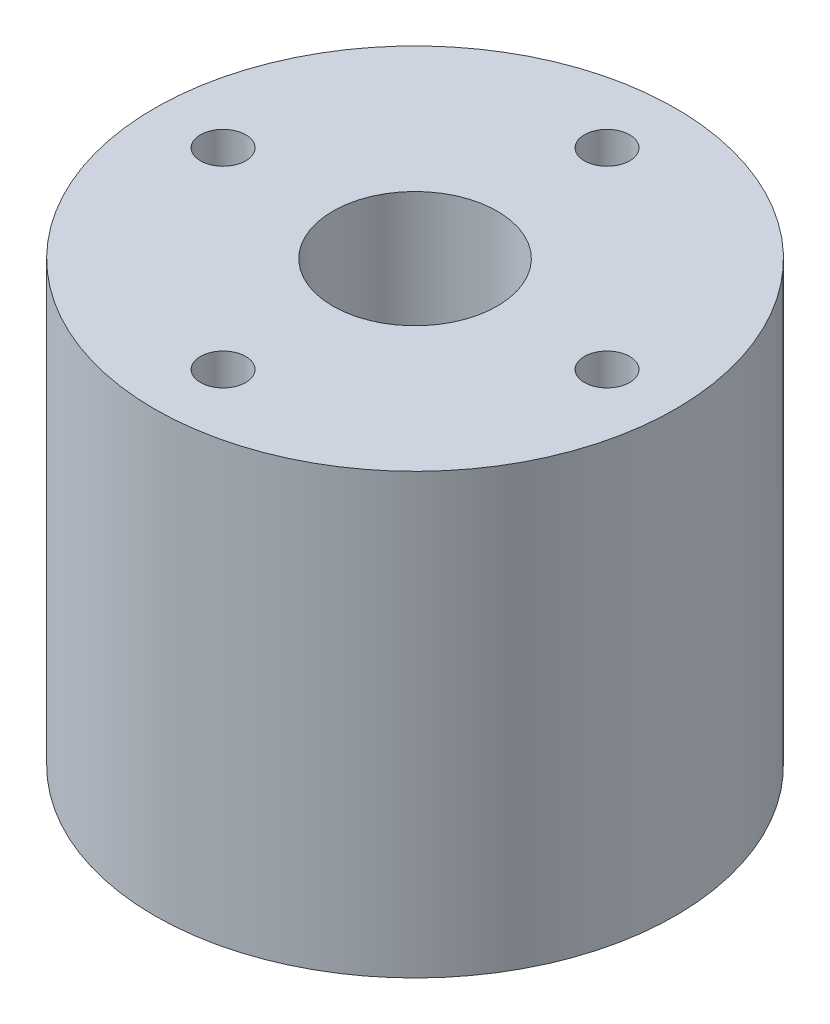
SolidWorks part; units mm, degrees
material "S45C表面镀硬铬"
ref_plane "前基準面" through (0, 0, 0) normal (0, 0, 1) x (1, 0, 0)
ref_plane "上基準面" through (0, 0, 0) normal (0, 1, 0) x (1, 0, 0)
ref_plane "右基準面" through (0, 0, 0) normal (1, 0, 0) x (0, 0, -1)
sketch "草图1" plane through (0, 0, 0) normal (0, 1, 0) x (1, 0, 0)
  circle A0 centre (0, 0) radius 19
  circle A1 centre (0, 0) radius 6
  dimension "D1" = 12
  dimension "D2" = 38
extrude "凸台-拉伸1" add sketch "草图1" along normal blind 32
sketch "草图2" plane through (0, 0, 0) normal (1, 0, 0) x (0, 0, -1)
  line L0 (0, 32) -> (0, 0) construction
  line L1 (19, 32) -> (-19, 32) construction
  line L2 (-19, 0) -> (19, 0) construction
  circle A0 centre (0, 16) radius 2.5
  dimension "D1" = 5
extrude "切除-拉伸1" cut sketch "草图2" against normal through all
hole_wizard "M4 螺纹孔1" positions "草图4" profile "草图3" tap size "M4" standard "ISO"
sketch "草图4" plane through (0, 32, 0) normal (0, 1, 0) x (-1, 0, 0)
  line L0 (0, 0) -> (-23.0317, 0) construction
  line L1 (0, 0) -> (0, 20.259) construction
  line L2 (0, 0) -> (24.292, 0) construction
  line L3 (0, 0) -> (0, -22.6397) construction
  circle A0 centre (0, 0) radius 14 construction
  point P0 (14, 0)
  point P19 (0, 14)
  point P21 (-14, 0)
  point P23 (0, -14)
  dimension "D1" = 28
sketch "草图3" plane through (-14, 32, 0) normal (1, 0, 0) x (0, 0, 1)
  line L0 (0, 0) -> (0, 11.0914)
  line L1 (0, 11.0914) -> (1.65, 10.1)
  line L2 (1.65, 10.1) -> (1.65, 0)
  line L5 (1.65, 0) -> (0, 0)
  line L10 (0, 11.0914) -> (-1.65, 10.1) construction
  line L11 (0, -6.35) -> (0, 107.95) construction
  dimension "螺纹孔钻头直径" = 3.3
  dimension "螺纹孔钻头深度" = 10.1
  dimension "导头角度" = 118
cosmetic thread "孔螺蚊线1" parameters "D1"=8, "D2"=4
cosmetic thread "孔螺蚊线2" parameters "D1"=8, "D2"=4
cosmetic thread "孔螺蚊线3" parameters "D1"=8, "D2"=4
cosmetic thread "孔螺蚊线4" parameters "D1"=8, "D2"=4
hole_wizard "M4 螺纹孔2" positions "草图6" profile "草图5" tap size "M4" standard "ISO"
sketch "草图6" plane through (0, 0, 0) normal (0, -1, 0) x (1, 0, 0)
  circle A0 centre (0, 0) radius 14 construction
  point P6 (0, 14)
  point P8 (-14, 0)
  point P10 (0, -14)
  point P12 (14, 0)
  dimension "D1" = 28
sketch "草图5" plane through (0, 0, 14) normal (1, 0, 0) x (0, 0, -1)
  line L0 (0, 0) -> (0, 11.0914)
  line L1 (0, 11.0914) -> (1.65, 10.1)
  line L2 (1.65, 10.1) -> (1.65, 0)
  line L5 (1.65, 0) -> (0, 0)
  line L10 (0, 11.0914) -> (-1.65, 10.1) construction
  line L11 (0, -6.35) -> (0, 107.95) construction
  dimension "螺纹孔钻头直径" = 3.3
  dimension "螺纹孔钻头深度" = 10.1
  dimension "导头角度" = 118
cosmetic thread "孔螺蚊线5" parameters "D1"=8, "D2"=4
cosmetic thread "孔螺蚊线6" parameters "D1"=8, "D2"=4
cosmetic thread "孔螺蚊线7" parameters "D1"=8, "D2"=4
cosmetic thread "孔螺蚊线8" parameters "D1"=8, "D2"=4
